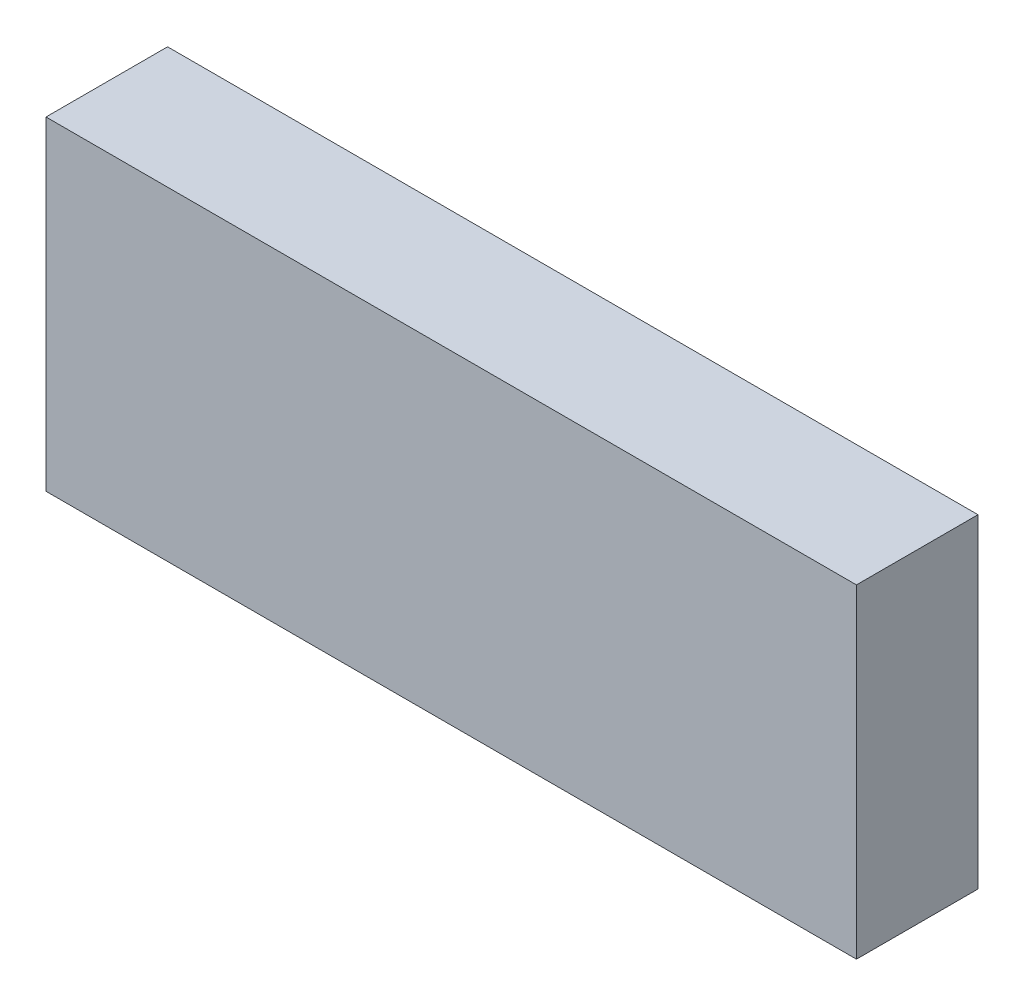
SolidWorks part; units mm, degrees
ref_plane "前视基准面" through (0, 0, 0) normal (0, 0, 1) x (1, 0, 0)
ref_plane "上视基准面" through (0, 0, 0) normal (0, 1, 0) x (1, 0, 0)
ref_plane "右视基准面" through (0, 0, 0) normal (1, 0, 0) x (0, 0, -1)
other "Configuration Table"
sketch "草图1" plane through (0, 0, 0) normal (0, 0, 1) x (1, 0, 0)
  line L0 (-40, 0) -> (40, 0)
  line L1 (40, 0) -> (40, 32)
  line L2 (40, 32) -> (-40, 32)
  line L3 (-40, 32) -> (-40, 0)
extrude "凸台-拉伸1" add sketch "草图1" along normal blind 12
